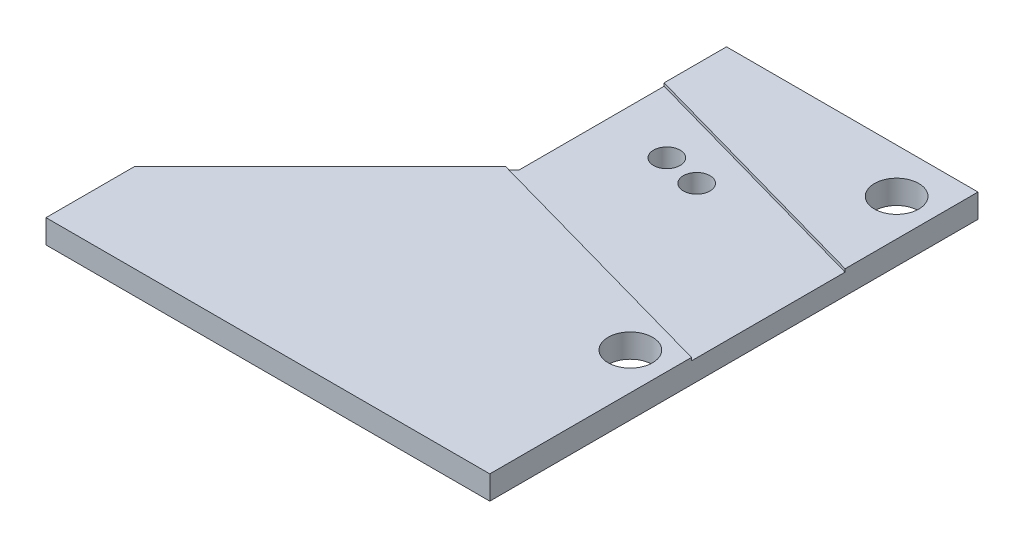
SolidWorks part; units mm, degrees
material "Cuivre"
ref_plane "Plan de face" through (0, 0, 0) normal (0, 0, 1) x (1, 0, 0)
ref_plane "Plan de dessus" through (0, 0, 0) normal (0, 1, 0) x (1, 0, 0)
ref_plane "Plan de droite" through (0, 0, 0) normal (1, 0, 0) x (0, 0, -1)
sketch "Esquisse1" plane through (0, 0, 0) normal (0, 1, 0) x (1, 0, 0)
  line L0 (-17, 12) -> (0, 12)
  line L1 (0, 12) -> (0, -21)
  line L2 (0, -21) -> (-30, -21)
  line L3 (-17, -2) -> (-17, 12)
  line L4 (0, 12) -> (-5, 12) construction
  line L6 (-102, -24) -> (3, -24) construction
  line L7 (-17, -2) -> (-30, -15)
  line L8 (-30, -15) -> (-30, -21)
  dimension "D1" = 17
  dimension "D2" = 3
  dimension "D3" = 45
  dimension "D4" = 30
  dimension "D5" = 14
  dimension "D6" = 33
  dimension "D7" = 6
extrude "Extrusion1" add sketch "Esquisse1" along normal blind 1.6
sketch "Esquisse2" plane through (0, 1.6, 0) normal (0, 1, 0) x (1, 0, 0)
  line L0 (-10.805, 3.3153) -> (-9.6268, 3.0878) construction
  line L1 (-13.3087, 3.7988) -> (-12.1305, 3.5713) construction
  circle A0 centre (-12.7196, 3.6851) radius 0.9
  circle A1 centre (-10.2159, 3.2016) radius 0.9
  dimension "D1" = 1.8
extrude "Enlèv. mat.-Extru.1" cut sketch "Esquisse2" against normal through all
sketch "Esquisse3" plane through (0, 1.6, 0) normal (0, 1, 0) x (1, 0, 0)
  line L4 (-17, 7.7828) -> (-17, -2)
  line L5 (-17.4707, -2.4707) -> (0, -7.3683)
  line L6 (-17, 7.7828) -> (-17, -2)
  line L7 (0, 3.0172) -> (-17, 7.7828)
  line L8 (0, -7.3683) -> (0, 3.0172)
  line L9 (-17.4707, -2.4707) -> (0, -7.3683)
  line L10 (0, -7.3683) -> (0, 3.0172)
  line L11 (0, 3.0172) -> (-17, 7.7828)
  line L146 (-17, -2) -> (-17.4707, -2.4707)
  line L147 (-17, -2) -> (-17.4707, -2.4707)
  dimension "D1" = 0
extrude "Enlèv. mat.-Extru.2" cut sketch "Esquisse3" against normal blind 0.2
sketch "Esquisse4" plane through (0, 1.6, 0) normal (0, 1, 0) x (1, 0, 0)
  line L0 (0, 3.0172) -> (0, 12) construction
  line L1 (0, 12) -> (-17, 12) construction
  line L3 (-9, -12) -> (3, -12) construction
  circle A0 centre (-2.5, 9) radius 1.5
  circle A1 centre (-2.5, -9) radius 1.5
  dimension "D1" = 2.5
  dimension "D4" = 3
  dimension "D2" = 3
  dimension "D3" = 3
extrude "Enlèv. mat.-Extru.3" cut sketch "Esquisse4" against normal through all
